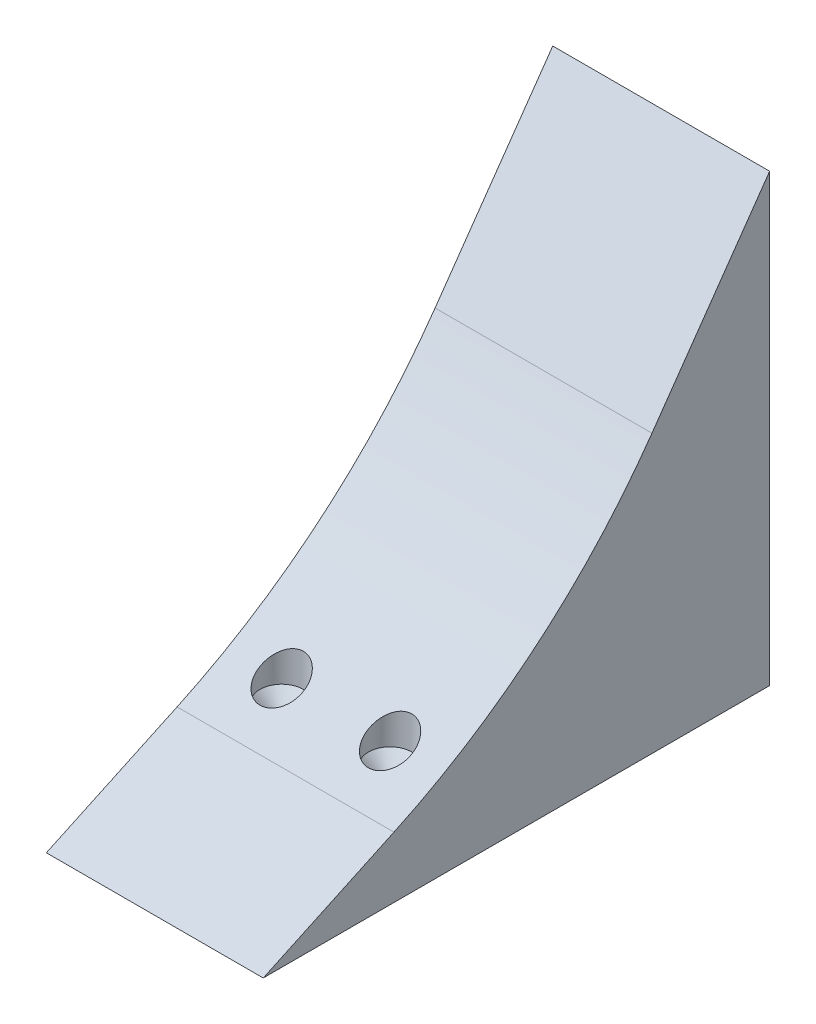
SolidWorks part; units mm, degrees
ref_plane "Front Plane" through (0, 0, 0) normal (0, 0, 1) x (1, 0, 0)
ref_plane "Top Plane" through (0, 0, 0) normal (0, 1, 0) x (1, 0, 0)
ref_plane "Right Plane" through (0, 0, 0) normal (1, 0, 0) x (0, 0, -1)
sketch "Sketch1" plane through (0, 0, 0) normal (1, 0, 0) x (0, 0, -1)
  line L0 (-61.4896, -124.3152) -> (57.1241, -124.3152)
  line L1 (57.1241, -124.3152) -> (57.1241, -19.9667)
  line L2 (29.5629, -59.3282) -> (57.1241, -19.9667)
  line L3 (-30.8689, -110.0365) -> (-61.4896, -124.3152)
  arc A0 (-30.8689, -110.0365) -> (29.5629, -59.3282) centre (-95.2759, 28.0848) ccw
  dimension "D2" = 152.4
  dimension "D1" = 55
  dimension "D3" = 25
extrude "Boss-Extrude1" add sketch "Sketch1" along normal blind 50.8
sketch "Sketch2" plane through (0, -124.3152, 0) normal (0, -1, 0) x (1, 0, 0)
  line L0 (12.7, 19.0759) -> (97.5645, 19.0759) construction
  line L1 (0, 61.4896) -> (0, -57.1241) construction
  line L2 (50.8, -57.1241) -> (0, -57.1241) construction
  circle A0 centre (12.7, 19.0759) radius 1.905
  circle A1 centre (38.1, 19.0759) radius 1.905
  dimension "D3" = 3.81
  dimension "D4" = 3.81
  dimension "D1" = 25.4
  dimension "D2" = 12.7
  dimension "D5" = 76.2
extrude "Cut-Extrude1" cut sketch "Sketch2" against normal blind 101.6
sketch "Sketch3" plane through (0, -124.3152, 0) normal (0, -1, 0) x (1, 0, 0)
  circle A0 centre (12.7, 19.0759) radius 5.08
  circle A1 centre (38.1, 19.0759) radius 5.08
  dimension "D1" = 10.16
  dimension "D2" = 10.16
extrude "Cut-Extrude2" cut sketch "Sketch3" against normal blind 101.6 from offset 12.7 offset against normal yes
chamfer "Chamfer1" distance 3.048 angle 45 2 edges at (38.1, -111.6152, 13.9959) (12.7, -111.6152, 13.9959)
